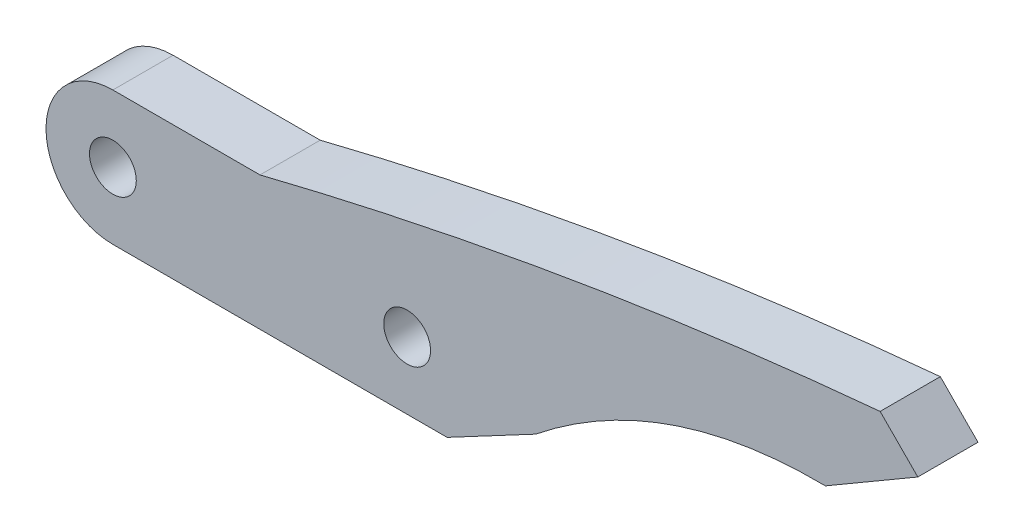
SolidWorks part; units mm, degrees
ref_plane "Front Plane" through (0, 0, 0) normal (0, 0, 1) x (1, 0, 0)
ref_plane "Top Plane" through (0, 0, 0) normal (0, 1, 0) x (1, 0, 0)
ref_plane "Right Plane" through (0, 0, 0) normal (1, 0, 0) x (0, 0, -1)
sketch "Sketch1" plane through (0, 0, 0) normal (0, 0, 1) x (1, 0, 0)
  line L0 (-11, 0) -> (11, 0) construction
  line L1 (0, 0) -> (0, 6.1468) construction
  line L3 (-16, 5) -> (16, 5)
  line L4 (-16, 5) -> (-16, -5)
  line L5 (-16, -5) -> (16, -5)
  line L6 (16, 5) -> (16, -5)
  line L7 (-16, 5) -> (16, -5) construction
  line L8 (-16, -5) -> (16, 5) construction
  circle A0 centre (-11, 0) radius 1.75
  circle A1 centre (-11, 0) radius 5
  circle A2 centre (11, 0) radius 1.75
  circle A3 centre (11, 0) radius 5
  point P4 (0, 0)
  dimension "D2" = 3.5
  dimension "D3" = 10
  dimension "D1" = 22
extrude "Boss-Extrude1" add sketch "Sketch1" along normal blind 4.5 contours A1 A0 | A3 A2 | L5 A3 L3 A1
sketch "Sketch2" plane through (0, 0, 4.5) normal (0, 0, 1) x (1, 0, 0)
  line L0 (46.364, 12.87) -> (49.1808, 10.03)
  line L1 (49.1808, 10.03) -> (42.27, 6)
  line L2 (-11, -5) -> (11, -5) construction
  line L3 (11, -5) -> (11, 0) construction
  line L4 (20.61, -1.48) -> (13.99, -5)
  line L5 (13.99, -5) -> (11, -5)
  line L6 (-11, 5) -> (11, 5) construction
  line L7 (0, 5) -> (11, 5)
  arc A0 (11, -5) -> (11, 5) centre (11, 0) ccw construction
  arc A1 (11, -5) -> (11, 5) centre (11, 0) ccw
  spline S0 degree 2 poles (42.27, 6) (30.1462, 6.1573) (20.61, -1.48) knots 0 0 0 1 1 1
  spline S1 degree 2 poles (0, 5) (22.8855, 10.7079) (46.364, 12.87) knots 0 0 0 1 1 1
  point P14 (12.495, -5)
  dimension "D1" = 4
  dimension "D2" = 8
  dimension "D3" = 17.87
  dimension "D4" = 15.03
  dimension "D5" = 11
  dimension "D6" = 9.45
  dimension "D7" = 3.52
  dimension "D8" = 9.61
  dimension "D9" = 20.52
  dimension "D10" = 31.27
  dimension "D11" = 2.99
  dimension "D12" = 28.001
  dimension "D13" = 13.52
  dimension "D14" = 15.07
extrude "Boss-Extrude2" add sketch "Sketch2" against normal up to surface (4.5 mm away) up to face at (-9.25, 0, 0)
